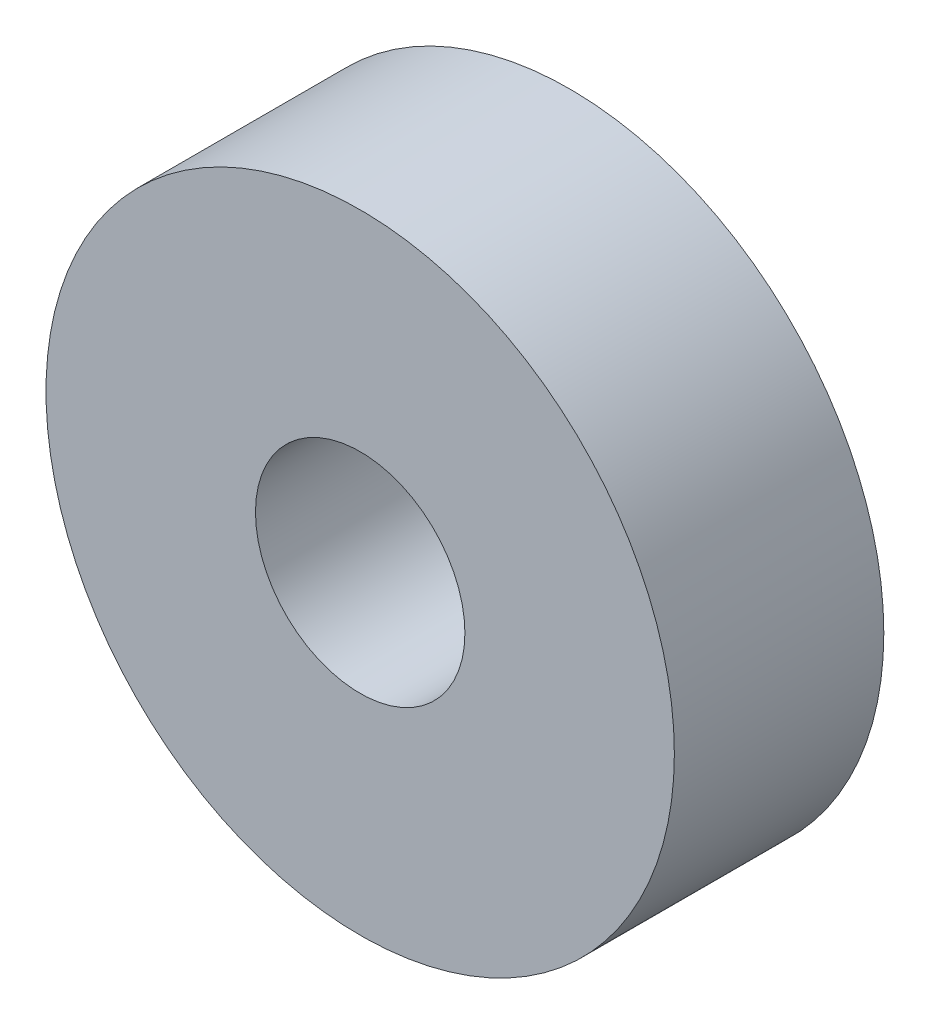
SolidWorks part; units mm, degrees
ref_plane "Front Plane" through (0, 0, 0) normal (0, 0, 1) x (1, 0, 0)
ref_plane "Top Plane" through (0, 0, 0) normal (0, 1, 0) x (1, 0, 0)
ref_plane "Right Plane" through (0, 0, 0) normal (1, 0, 0) x (0, 0, -1)
sketch "Sketch1" plane through (0, 0, 0) normal (0, 0, 1) x (1, 0, 0)
  circle A0 centre (0, 0) radius 38.1
  circle A1 centre (0, 0) radius 12.7
  dimension "D1" = 76.2
  dimension "D2" = 25.4
extrude "Boss-Extrude1" add sketch "Sketch1" along normal blind 25.4
equation "\"Thick\"= \"in\""
